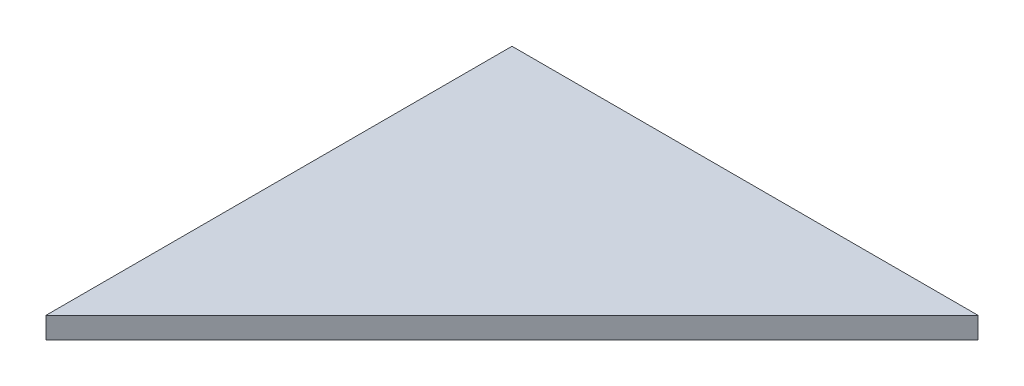
SolidWorks part; units mm, degrees
ref_plane "Front Plane" through (0, 0, 0) normal (0, 0, 1) x (1, 0, 0)
ref_plane "Top Plane" through (0, 0, 0) normal (0, 1, 0) x (1, 0, 0)
ref_plane "Right Plane" through (0, 0, 0) normal (1, 0, 0) x (0, 0, -1)
sketch "Sketch1" plane through (0, 0, 0) normal (0, 1, 0) x (1, 0, 0)
  line L1 (0, 0) -> (69.85, 0)
  line L2 (0, 0) -> (0, 69.85)
  line L3 (0, 69.85) -> (69.85, 69.85)
  line L4 (69.85, 0) -> (69.85, 69.85)
  dimension "D1" = 69.85
  dimension "D2" = 69.85
extrude "Boss-Extrude1" add sketch "Sketch1" along normal blind 3.175
sketch "Sketch2" plane through (0, 3.175, 0) normal (0, 1, 0) x (1, 0, 0)
  line L0 (0, 0) -> (69.85, 69.85)
extrude "Cut-Extrude2" cut sketch "Sketch2" against normal blind 3.175 and the other way through all flip side to cut
